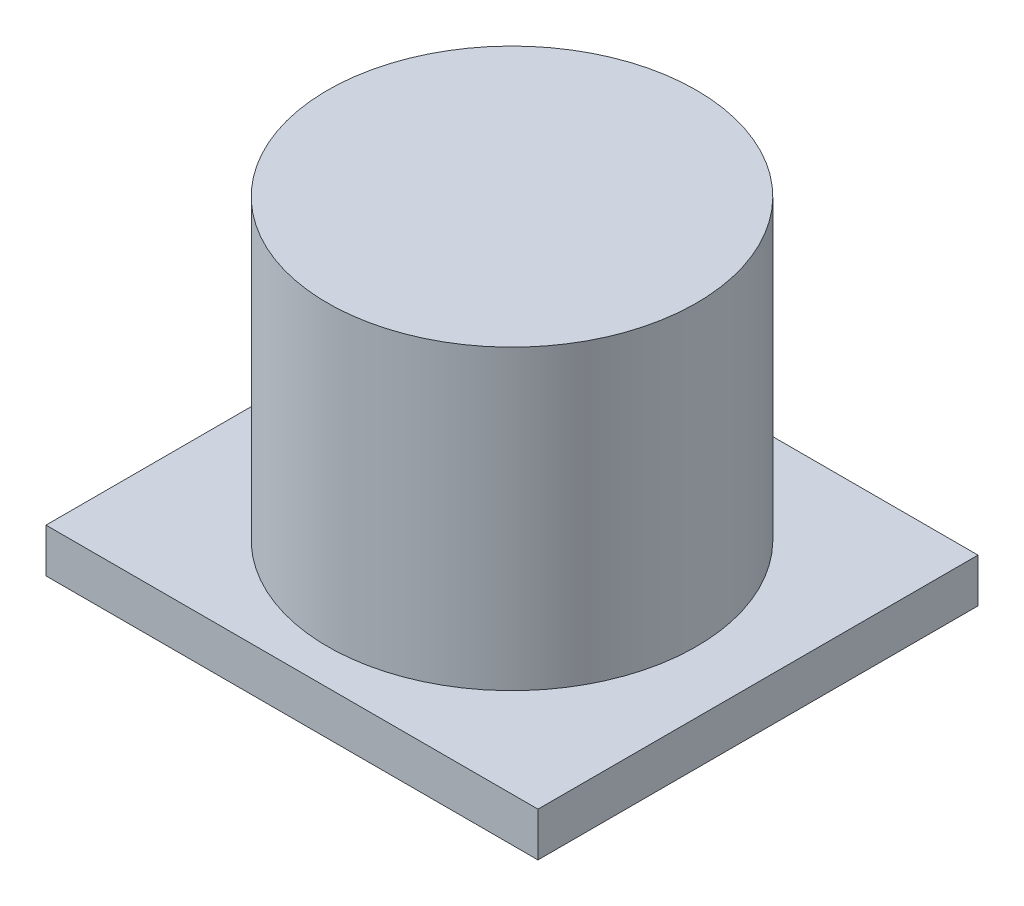
SolidWorks part; units mm, degrees
ref_plane "Front Plane" through (0, 0, 0) normal (0, 0, 1) x (1, 0, 0)
ref_plane "Top Plane" through (0, 0, 0) normal (0, 1, 0) x (1, 0, 0)
ref_plane "Right Plane" through (0, 0, 0) normal (1, 0, 0) x (0, 0, -1)
sketch "Sketch1" plane through (0, 0, 0) normal (0, 1, 0) x (1, 0, 0)
  line L1 (-11.18, -10) -> (11.18, -10)
  line L2 (-11.18, -10) -> (-11.18, 10)
  line L3 (-11.18, 10) -> (11.18, 10)
  line L4 (11.18, -10) -> (11.18, 10)
  line L5 (-11.18, -10) -> (11.18, 10) construction
  line L6 (-11.18, 10) -> (11.18, -10) construction
  point P1 (0, 0)
  dimension "D1" = 22.36
  dimension "D2" = 20
extrude "Boss-Extrude1" add sketch "Sketch1" along normal blind 2
sketch "Sketch2" plane through (0, 2, 0) normal (0, 1, 0) x (1, 0, 0)
  circle A0 centre (0, 0) radius 8.382
  dimension "D1" = 16.764
extrude "Boss-Extrude2" add sketch "Sketch2" along normal blind 13.52
